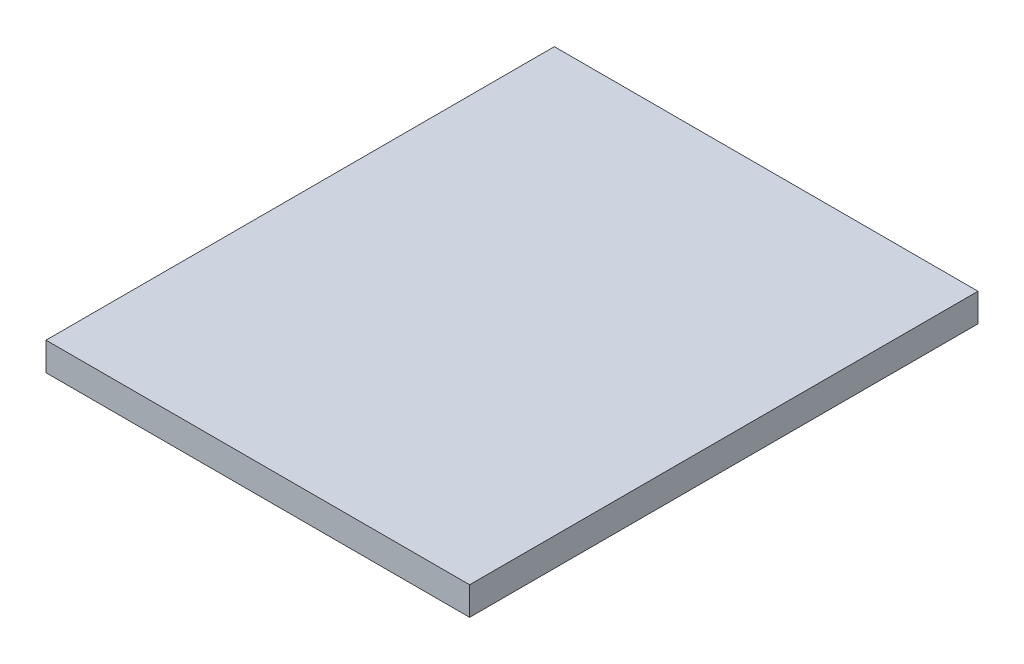
SolidWorks part; units mm, degrees
ref_plane "Front Plane" through (0, 0, 0) normal (0, 0, 1) x (1, 0, 0)
ref_plane "Top Plane" through (0, 0, 0) normal (0, 1, 0) x (1, 0, 0)
ref_plane "Right Plane" through (0, 0, 0) normal (1, 0, 0) x (0, 0, -1)
sketch "Sketch1" plane through (0, 0, 0) normal (0, 1, 0) x (1, 0, 0)
  line L1 (-47.625, -57.15) -> (47.625, -57.15)
  line L2 (-47.625, -57.15) -> (-47.625, 57.15)
  line L3 (-47.625, 57.15) -> (47.625, 57.15)
  line L4 (47.625, -57.15) -> (47.625, 57.15)
  line L5 (-47.625, -57.15) -> (47.625, 57.15) construction
  line L6 (-47.625, 57.15) -> (47.625, -57.15) construction
  point P0 (0, 0)
  point P6 (0, 0)
  dimension "D1" = 95.25
  dimension "D2" = 114.3
extrude "Boss-Extrude1" add sketch "Sketch1" along normal mid plane 6.35
